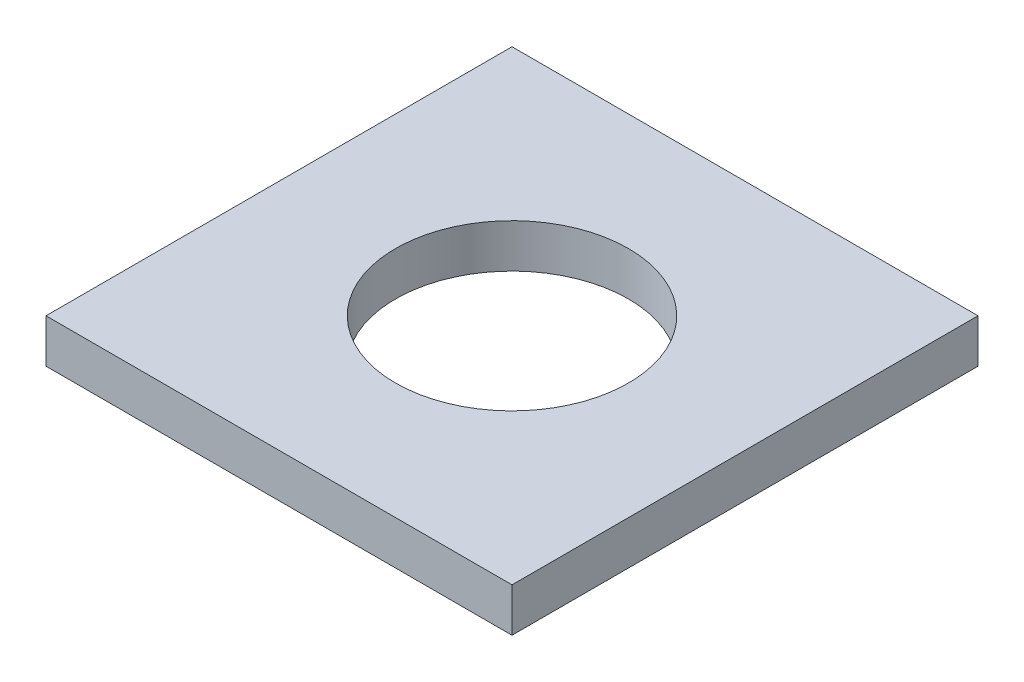
SolidWorks part; units mm, degrees
ref_plane "Front Plane" through (0, 0, 0) normal (0, 0, 1) x (1, 0, 0)
ref_plane "Top Plane" through (0, 0, 0) normal (0, 1, 0) x (1, 0, 0)
ref_plane "Right Plane" through (0, 0, 0) normal (1, 0, 0) x (0, 0, -1)
sketch "Sketch1" plane through (0, 0, 0) normal (0, 1, 0) x (1, 0, 0)
  line L1 (-25.4, 25.4) -> (25.4, 25.4)
  line L2 (-25.4, 25.4) -> (-25.4, -25.4)
  line L3 (-25.4, -25.4) -> (25.4, -25.4)
  line L4 (25.4, 25.4) -> (25.4, -25.4)
  line L5 (-25.4, 25.4) -> (25.4, -25.4) construction
  line L6 (-25.4, -25.4) -> (25.4, 25.4) construction
  point P0 (0, 0)
  dimension "D1" = 50.8
  dimension "D2" = 50.8
extrude "Boss-Extrude1" add sketch "Sketch1" along normal blind 4.7625
sketch "Sketch2" plane through (0, 4.7625, 0) normal (0, 1, 0) x (1, 0, 0)
  circle A0 centre (0, 0) radius 12.7
  dimension "D1" = 25.4
extrude "Cut-Extrude1" cut sketch "Sketch2" against normal up to next
